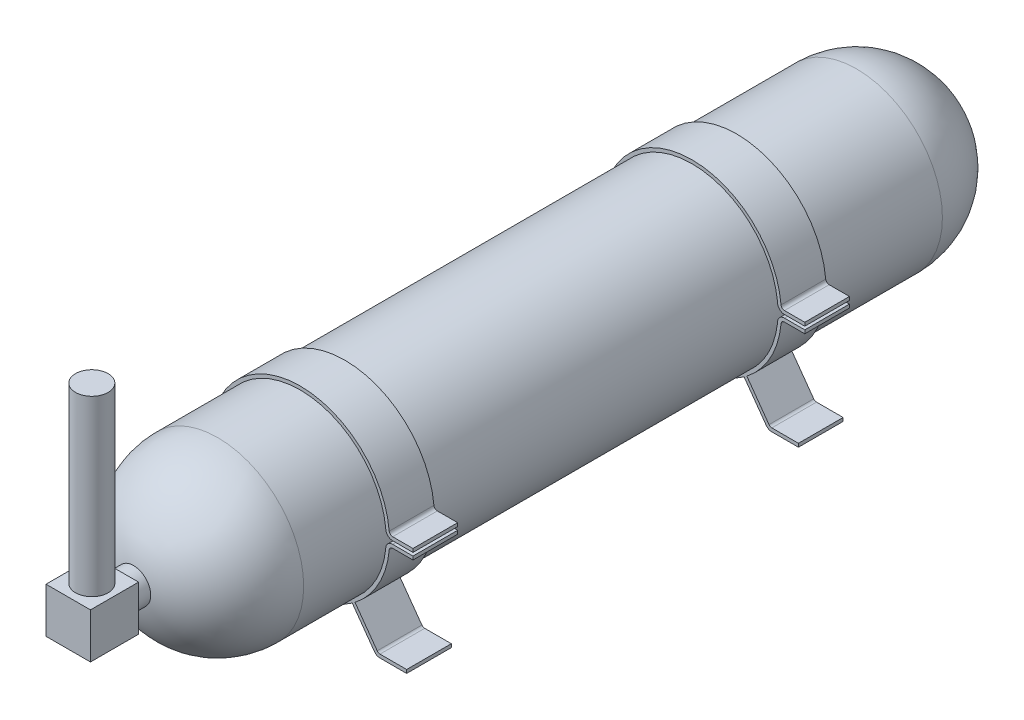
SolidWorks part; units mm, degrees
ref_plane "Front Plane" through (0, 0, 0) normal (0, 0, 1) x (1, 0, 0)
ref_plane "Top Plane" through (0, 0, 0) normal (0, 1, 0) x (1, 0, 0)
ref_plane "Right Plane" through (0, 0, 0) normal (1, 0, 0) x (0, 0, -1)
sketch "Sketch1" plane through (0, 0, 0) normal (1, 0, 0) x (0, 0, -1)
  line L0 (0, 0) -> (1858.4337, 0) construction
  line L1 (0, 250) -> (1858.4337, 250)
  line L3 (-250, 0) -> (2108.4337, 0)
  arc A0 (0, 250) -> (-250, 0) centre (0, 0) ccw
  arc A1 (2108.4337, 0) -> (1858.4337, 250) centre (1858.4337, 0) ccw
  point P3 (929.2169, 0)
revolve "Revolve1" add sketch "Sketch1" angle 360 about L0
ref_plane "Plane1" through (0, 0, -240) normal (0, 0, 1) x (1, 0, 0)
sketch "Sketch2" plane through (0, 0, -240) normal (0, 0, 1) x (1, 0, 0)
  line L0 (-151.4249, -211.3539) -> (-215.8243, -301.2405)
  line L2 (-268.8811, 4.5546) -> (-328.0099, 4.5546)
  line L3 (328.0099, 4.5546) -> (328.0099, 14.5546)
  line L4 (-268.8811, 14.5546) -> (-328.0099, 14.5546)
  line L5 (-328.0099, 4.5546) -> (-328.0099, 14.5546)
  line L6 (268.8811, 14.5546) -> (328.0099, 14.5546)
  line L7 (268.8811, 4.5546) -> (328.0099, 4.5546)
  line L8 (268.8811, -4.5546) -> (328.0099, -4.5546)
  line L9 (268.8811, -14.5546) -> (328.0099, -14.5546)
  line L10 (-328.0099, -4.5546) -> (-328.0099, -14.5546)
  line L11 (-268.8811, -14.5546) -> (-328.0099, -14.5546)
  line L12 (328.0099, -4.5546) -> (328.0099, -14.5546)
  line L13 (-268.8811, -4.5546) -> (-328.0099, -4.5546)
  line L14 (-232.0823, -309.5925) -> (-309.5838, -309.5925)
  line L15 (159.4419, -205.3735) -> (223.9533, -295.4165)
  line L16 (-159.4419, -205.3735) -> (-223.9533, -295.4165)
  line L17 (-232.0823, -299.5925) -> (-309.5838, -299.5925)
  line L18 (-309.5838, -299.5925) -> (-309.5838, -309.5925)
  line L19 (151.4249, -211.3539) -> (215.8243, -301.2405)
  line L20 (0, 0) -> (-215.8243, -301.2405) construction
  line L21 (10, 31.1279) -> (-223.9533, -295.4165) construction
  line L22 (10, 31.1279) -> (10, -112.2388) construction
  line L23 (0, 0) -> (0, -112.2388) construction
  line L24 (309.5838, -299.5925) -> (309.5838, -309.5925)
  line L25 (232.0823, -299.5925) -> (309.5838, -299.5925)
  line L26 (232.0823, -309.5925) -> (309.5838, -309.5925)
  arc A0 (268.8811, 4.5546) -> (248.964, 22.7358) centre (268.8811, 24.5546) cw
  arc A1 (248.964, 22.7358) -> (-248.964, 22.7358) centre (0, 0) ccw
  arc A2 (258.9226, 23.6452) -> (-258.9226, 23.6452) centre (0, 0) ccw
  arc A3 (-268.8811, 14.5546) -> (-258.9226, 23.6452) centre (-268.8811, 24.5546) ccw
  circle A4 centre (0, 0) radius 250 construction
  circle A5 centre (0, 0) radius 260 construction
  arc A6 (-268.8811, 4.5546) -> (-248.964, 22.7358) centre (-268.8811, 24.5546) ccw
  arc A7 (268.8811, 14.5546) -> (258.9226, 23.6452) centre (268.8811, 24.5546) cw
  arc A8 (268.8811, -14.5546) -> (258.9226, -23.6452) centre (268.8811, -24.5546) ccw
  arc A9 (-268.8811, -4.5546) -> (-248.964, -22.7358) centre (-268.8811, -24.5546) cw
  arc A10 (-268.8811, -14.5546) -> (-258.9226, -23.6452) centre (-268.8811, -24.5546) cw
  arc A11 (258.9226, -23.6452) -> (159.4419, -205.3735) centre (0, 0) cw
  arc A12 (248.964, -22.7358) -> (-248.964, -22.7358) centre (0, 0) cw
  arc A13 (268.8811, -4.5546) -> (248.964, -22.7358) centre (268.8811, -24.5546) ccw
  arc A14 (-215.8243, -301.2405) -> (-232.0823, -309.5925) centre (-232.0823, -289.5925) cw
  arc A15 (-223.9533, -295.4165) -> (-232.0823, -299.5925) centre (-232.0823, -289.5925) cw
  arc A16 (-159.4419, -205.3735) -> (-258.9226, -23.6452) centre (0, 0) cw
  arc A17 (223.9533, -295.4165) -> (232.0823, -299.5925) centre (232.0823, -289.5925) ccw
  arc A18 (215.8243, -301.2405) -> (232.0823, -309.5925) centre (232.0823, -289.5925) ccw
  arc A19 (151.4249, -211.3539) -> (-151.4249, -211.3539) centre (0, 0) cw
  point P3 (260, 0)
  point P13 (239.0762, 73.0929)
  dimension "D3" = 10
  dimension "D4" = 20
  dimension "D5" = 20
  dimension "D2" = 10
  dimension "D1" = 10
  dimension "D6" = 10
extrude "Boss-Extrude1" add sketch "Sketch2" against normal blind 130 separate body
pattern_linear "LPattern1" count 2 spacing 1140 along (0, 0, -1) of "Boss-Extrude1"
sketch "Sketch3" plane through (0, 0, 0) normal (0, 0, 1) x (1, 0, 0)
  circle A0 centre (0, 0) radius 50
  dimension "D1" = 100
extrude "Boss-Extrude2" add sketch "Sketch3" along normal blind 295
sketch "Sketch4" plane through (0, 0, 295) normal (0, 0, 1) x (1, 0, 0)
  line L0 (-64.7006, -65.6901) -> (-64.7006, 65.6901)
  line L3 (-64.7006, 65.6901) -> (64.7006, 65.6901)
  line L4 (64.7006, -65.6901) -> (64.7006, 65.6901)
  line L5 (-64.7006, -65.6901) -> (64.7006, -65.6901)
  point P10 (0, 0)
extrude "Boss-Extrude3" add sketch "Sketch4" along normal blind 140
sketch "Sketch5" plane through (0, 65.6901, 0) normal (0, 1, 0) x (1, 0, 0)
  circle A0 centre (0, -366.3791) radius 47.3947
extrude "Boss-Extrude4" add sketch "Sketch5" along normal blind 505
